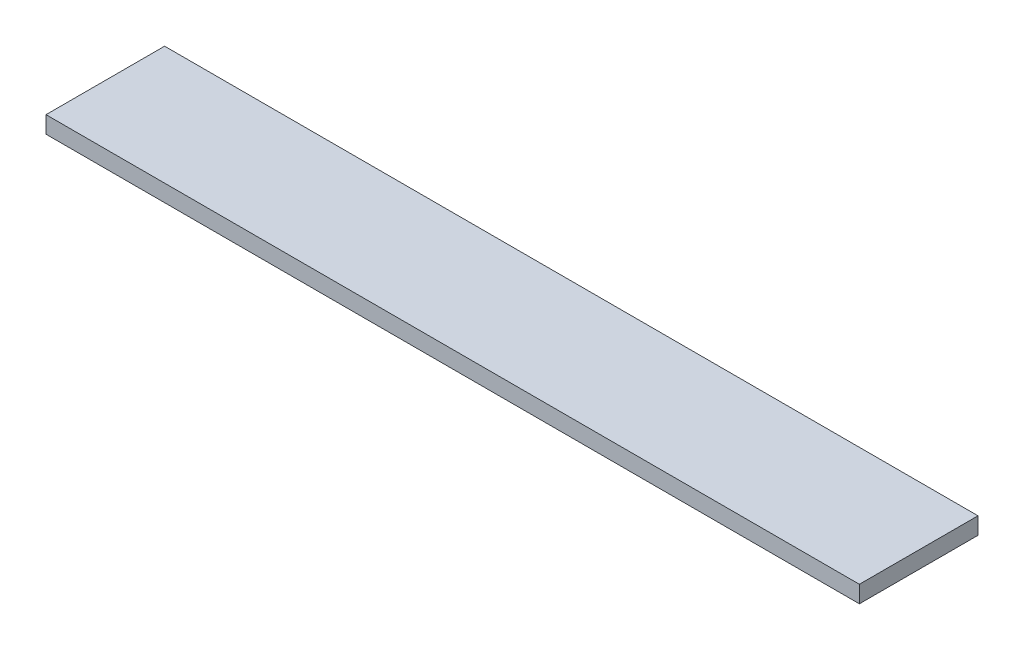
SolidWorks part; units mm, degrees
ref_plane "Front Plane" through (0, 0, 0) normal (0, 0, 1) x (1, 0, 0)
ref_plane "Top Plane" through (0, 0, 0) normal (0, 1, 0) x (1, 0, 0)
ref_plane "Right Plane" through (0, 0, 0) normal (1, 0, 0) x (0, 0, -1)
sketch "Sketch1" plane through (0, 0, 0) normal (0, 1, 0) x (1, 0, 0)
  line L0 (-314.325, -127) -> (-255.5763, -127) construction
  line L1 (-304.8, -88.9) -> (304.8, -88.9)
  line L2 (-304.8, -88.9) -> (-304.8, 0)
  line L3 (-304.8, 0) -> (304.8, 0)
  line L4 (304.8, -88.9) -> (304.8, 0)
  line L5 (-304.8, -88.9) -> (304.8, 0) construction
  line L6 (-304.8, 0) -> (304.8, -88.9) construction
  line L7 (314.325, -127) -> (314.325, 9.525) construction
  line L8 (304.8, -88.9) -> (314.325, -88.9) construction
  line L9 (-304.8, -88.9) -> (-314.325, -88.9) construction
  line L10 (-314.325, 9.525) -> (-314.325, -127) construction
  dimension "D1" = 9.525
  dimension "D2" = 38.1
extrude "Boss-Extrude1" add sketch "Sketch1" against normal blind 12.7
